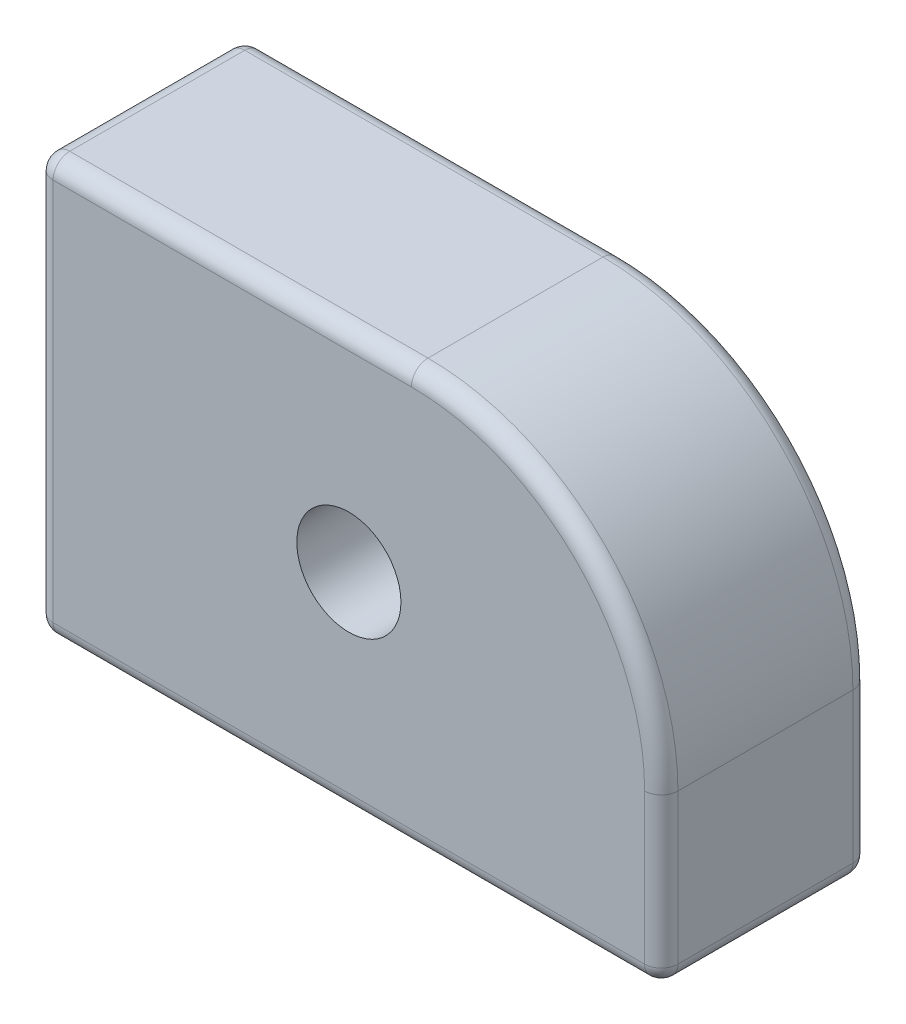
SolidWorks part; units mm, degrees
ref_plane "Front Plane" through (0, 0, 0) normal (0, 0, 1) x (1, 0, 0)
ref_plane "Top Plane" through (0, 0, 0) normal (0, 1, 0) x (1, 0, 0)
ref_plane "Right Plane" through (0, 0, 0) normal (1, 0, 0) x (0, 0, -1)
sketch "Sketch1" plane through (0, 0, 0) normal (0, 0, 1) x (1, 0, 0)
  line L0 (0, 0) -> (0, -50) construction
  line L1 (-75, -50) -> (75, -50)
  line L2 (-75, -50) -> (-75, 50)
  line L3 (-75, 50) -> (15, 50)
  line L4 (75, -10) -> (75, -50)
  circle A0 centre (0, 0) radius 12.5
  arc A1 (15, 50) -> (75, -10) centre (15, -10) cw
  point P7 (0, -50)
  dimension "D1" = 25
  dimension "D5" = 60
  dimension "D2" = 50
  dimension "D3" = 150
  dimension "D4" = 100
extrude "Boss-Extrude1" add sketch "Sketch1" against normal mid plane 50 contours A0
sketch "Sketch2" plane through (-75, 0, 0) normal (-1, 0, 0) x (0, 0, 1)
  circle A0 centre (0, 0) radius 15
  dimension "D1" = 30
extrude "Cut-Extrude1" cut sketch "Sketch2" against normal blind 60
fillet "Fillet1" radius 4 13 edges at (57.4264, 32.4264, 25) (75, -30, 25) (0, -50, 25) (-75, 0, 25) (-30, 50, 25) (0, -50, -25) (-75, 0, -25) (-75, -50, 0) (-75, 50, 0) (75, -50, 0) (75, -30, -25) (57.4264, 32.4264, -25) (-30, 50, -25)
